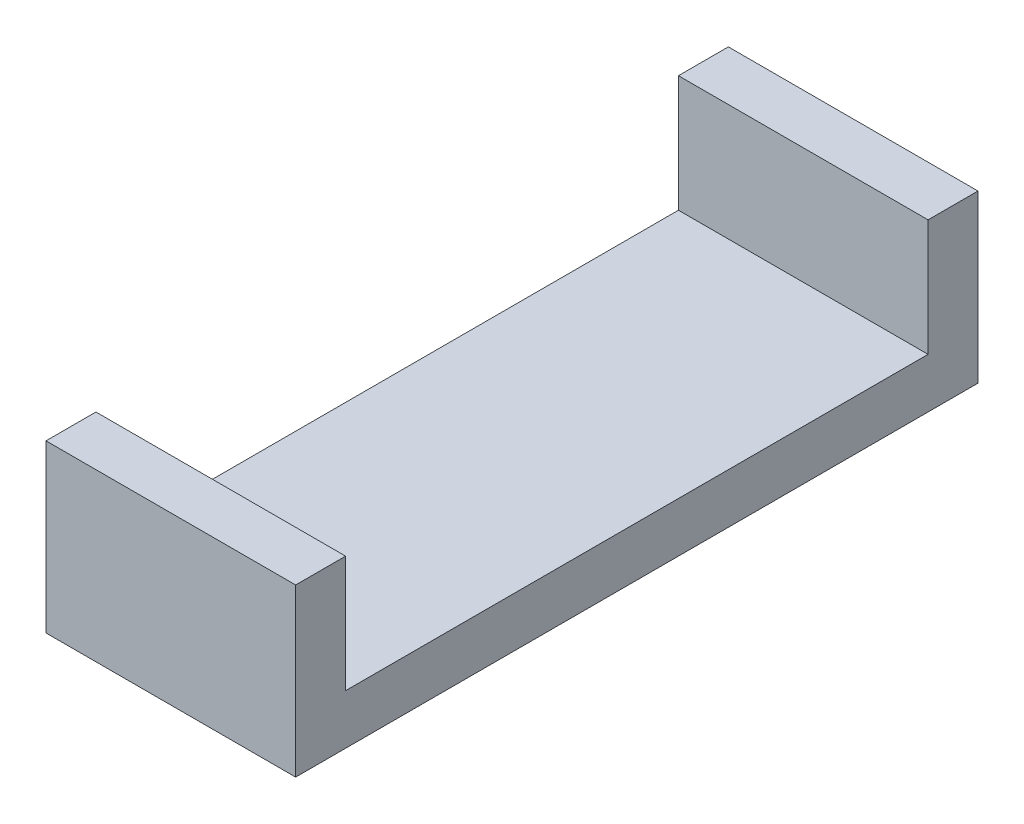
SolidWorks part; units mm, degrees
ref_plane "Front Plane" through (0, 0, 0) normal (0, 0, 1) x (1, 0, 0)
ref_plane "Top Plane" through (0, 0, 0) normal (0, 1, 0) x (1, 0, 0)
ref_plane "Right Plane" through (0, 0, 0) normal (1, 0, 0) x (0, 0, -1)
sketch "Sketch1" plane through (0, 0, 0) normal (0, 1, 0) x (1, 0, 0)
  line L1 (-7.5, 20.5) -> (7.5, 20.5)
  line L2 (-7.5, 20.5) -> (-7.5, -20.5)
  line L3 (-7.5, -20.5) -> (7.5, -20.5)
  line L4 (7.5, 20.5) -> (7.5, -20.5)
  line L5 (-7.5, 20.5) -> (7.5, -20.5) construction
  line L6 (-7.5, -20.5) -> (7.5, 20.5) construction
  point P0 (0, 0)
extrude "Boss-Extrude3" add sketch "Sketch1" along normal blind 3
sketch "Sketch3" plane through (0, 3, 0) normal (0, 1, 0) x (1, 0, 0)
  line L0 (7.5, -20.5) -> (7.5, -17.5)
  line L1 (7.5, -20.5) -> (7.5, 20.5) construction
  line L2 (7.5, -17.5) -> (-7.5, -17.5)
  line L3 (-7.5, 20.5) -> (-7.5, -20.5) construction
  line L4 (-7.5, -17.5) -> (-7.5, -20.5)
  line L5 (-7.5, -20.5) -> (7.5, -20.5)
extrude "Boss-Extrude4" add sketch "Sketch3" along normal blind 7
sketch "Sketch4" plane through (0, 3, 0) normal (0, 1, 0) x (1, 0, 0)
  line L0 (-7.5, 20.5) -> (7.5, 20.5)
  line L8 (7.5, 20.5) -> (7.5, 17.5)
  line L9 (7.5, -17.5) -> (7.5, 20.5) construction
  line L10 (7.5, 17.5) -> (-7.5, 17.5)
  line L11 (-7.5, 20.5) -> (-7.5, -17.5) construction
  line L12 (-7.5, 17.5) -> (-7.5, 20.5)
extrude "Boss-Extrude5" add sketch "Sketch4" along normal blind 7
